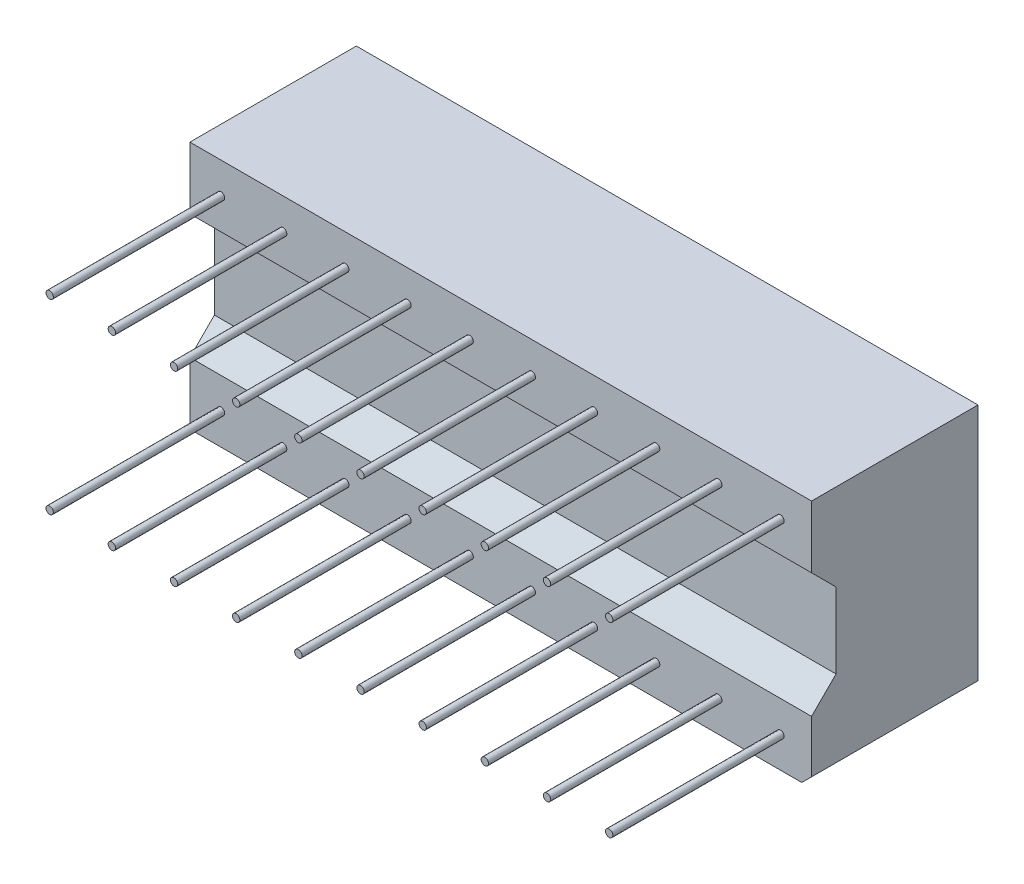
SolidWorks part; units mm, degrees
ref_plane "Front Plane" through (0, 0, 0) normal (0, 0, 1) x (1, 0, 0)
ref_plane "Top Plane" through (0, 0, 0) normal (0, 1, 0) x (1, 0, 0)
ref_plane "Right Plane" through (0, 0, 0) normal (1, 0, 0) x (0, 0, -1)
sketch "Sketch1" plane through (0, 0, 0) normal (0, 0, 1) x (1, 0, 0)
  line L0 (0, 72.8671) -> (0, -91.424) construction
  line L1 (-128.9091, 0) -> (127.9194, 0) construction
  line L3 (-12.7, 5.08) -> (12.7, 5.08)
  line L4 (-12.7, 5.08) -> (-12.7, -5.08)
  line L5 (-12.7, -5.08) -> (12.7, -5.08)
  line L6 (12.7, 5.08) -> (12.7, -5.08)
  dimension "D1" = 25.4
  dimension "D2" = 12.7
  dimension "D3" = 10.16
  dimension "D4" = 5.08
extrude "Boss-Extrude1" add sketch "Sketch1" against normal blind 6.8
sketch "Sketch2" plane through (-12.7, 0, 0) normal (-1, 0, 0) x (0, 0, 1)
  line L0 (-10.6638, 0) -> (5.8503, 0) construction
  line L1 (0, -2.54) -> (0, 2.54)
  line L2 (0, 5.08) -> (0, -5.08) construction
  line L3 (0, 2.54) -> (-1, 1.54)
  line L4 (-1, 1.54) -> (-1, -1.54)
  line L6 (0, -2.54) -> (-1, -1.54)
  point P10 (-1, 0)
  point P11 (0, 0)
  dimension "D1" = 2.54
  dimension "D2" = 1
  dimension "D3" = 45
extrude "Cut-Extrude1" cut sketch "Sketch2" against normal through all
sketch "Sketch3" plane through (0, 0, 0) normal (0, 0, 1) x (1, 0, 0)
  line L0 (-16.0452, 0) -> (15.0455, 0) construction
  line L1 (12.7, 5.08) -> (-12.7, 5.08) construction
  line L2 (12.7, 2.54) -> (12.7, 5.08) construction
  line L3 (-12.7, 5.08) -> (-12.7, 2.54) construction
  circle A0 centre (11.43, 3.81) radius 0.15
  circle A1 centre (8.89, 3.81) radius 0.15
  circle A2 centre (6.35, 3.81) radius 0.15
  circle A3 centre (3.81, 3.81) radius 0.15
  circle A4 centre (1.27, 3.81) radius 0.15
  circle A5 centre (-1.27, 3.81) radius 0.15
  circle A6 centre (-3.81, 3.81) radius 0.15
  circle A7 centre (-6.35, 3.81) radius 0.15
  circle A8 centre (-8.89, 3.81) radius 0.15
  circle A9 centre (-11.43, 3.81) radius 0.15
  circle A10 centre (-11.43, -3.81) radius 0.15
  circle A11 centre (-8.89, -3.81) radius 0.15
  circle A12 centre (-6.35, -3.81) radius 0.15
  circle A13 centre (-3.81, -3.81) radius 0.15
  circle A14 centre (-1.27, -3.81) radius 0.15
  circle A15 centre (1.27, -3.81) radius 0.15
  circle A16 centre (3.81, -3.81) radius 0.15
  circle A17 centre (6.35, -3.81) radius 0.15
  circle A18 centre (8.89, -3.81) radius 0.15
  circle A19 centre (11.43, -3.81) radius 0.15
  dimension "D1" = 1.27
  dimension "D2" = 0.3
  dimension "D3" = 1.27
  dimension "D5" = 1.27
  dimension "D6" = 1.27
  dimension "D4" = 10
extrude "Boss-Extrude2" add sketch "Sketch3" along normal blind 7 separate body
sketch "Sketch4" plane through (0, 0, -6.8) normal (0, 0, -1) x (-1, 0, 0)
  line L0 (-15.2455, 0) -> (15.6703, 0) construction
  line L1 (12.7, 5.08) -> (12.7, -5.08) construction
  line L2 (10.56, 2.5) -> (12.3, 2.5)
  line L3 (10.56, 2.5) -> (10.56, -2.5)
  line L4 (10.56, -2.5) -> (12.3, -2.5)
  line L5 (12.3, 2.5) -> (12.3, -2.5)
  line L6 (8.02, 2.5) -> (9.76, 2.5)
  line L7 (8.02, 2.5) -> (8.02, -2.5)
  line L8 (8.02, -2.5) -> (9.76, -2.5)
  line L9 (9.76, 2.5) -> (9.76, -2.5)
  line L10 (5.48, 2.5) -> (7.22, 2.5)
  line L11 (5.48, 2.5) -> (5.48, -2.5)
  line L12 (5.48, -2.5) -> (7.22, -2.5)
  line L13 (7.22, 2.5) -> (7.22, -2.5)
  line L14 (2.94, 2.5) -> (4.68, 2.5)
  line L15 (2.94, 2.5) -> (2.94, -2.5)
  line L16 (2.94, -2.5) -> (4.68, -2.5)
  line L17 (4.68, 2.5) -> (4.68, -2.5)
  line L18 (0.4, 2.5) -> (2.14, 2.5)
  line L19 (0.4, 2.5) -> (0.4, -2.5)
  line L20 (0.4, -2.5) -> (2.14, -2.5)
  line L21 (2.14, 2.5) -> (2.14, -2.5)
  line L22 (-2.14, 2.5) -> (-0.4, 2.5)
  line L23 (-2.14, 2.5) -> (-2.14, -2.5)
  line L24 (-2.14, -2.5) -> (-0.4, -2.5)
  line L25 (-0.4, 2.5) -> (-0.4, -2.5)
  line L26 (-4.68, 2.5) -> (-2.94, 2.5)
  line L27 (-4.68, 2.5) -> (-4.68, -2.5)
  line L28 (-4.68, -2.5) -> (-2.94, -2.5)
  line L29 (-2.94, 2.5) -> (-2.94, -2.5)
  line L30 (-7.22, 2.5) -> (-5.48, 2.5)
  line L31 (-7.22, 2.5) -> (-7.22, -2.5)
  line L32 (-7.22, -2.5) -> (-5.48, -2.5)
  line L33 (-5.48, 2.5) -> (-5.48, -2.5)
  line L34 (-9.76, 2.5) -> (-8.02, 2.5)
  line L35 (-9.76, 2.5) -> (-9.76, -2.5)
  line L36 (-9.76, -2.5) -> (-8.02, -2.5)
  line L37 (-8.02, 2.5) -> (-8.02, -2.5)
  line L38 (-12.3, 2.5) -> (-10.56, 2.5)
  line L39 (-12.3, 2.5) -> (-12.3, -2.5)
  line L40 (-12.3, -2.5) -> (-10.56, -2.5)
  line L41 (-10.56, 2.5) -> (-10.56, -2.5)
  dimension "D1" = 5
  dimension "D2" = 2.5
  dimension "D3" = 1.74
  dimension "D4" = 0.4
  dimension "D5" = 10
extrude "Cut-Extrude2" cut sketch "Sketch4" against normal blind 0.1
chamfer "Chamfer1" distance 0.4 angle 45 1 edges at (12.7, -5.08, -3.4)
